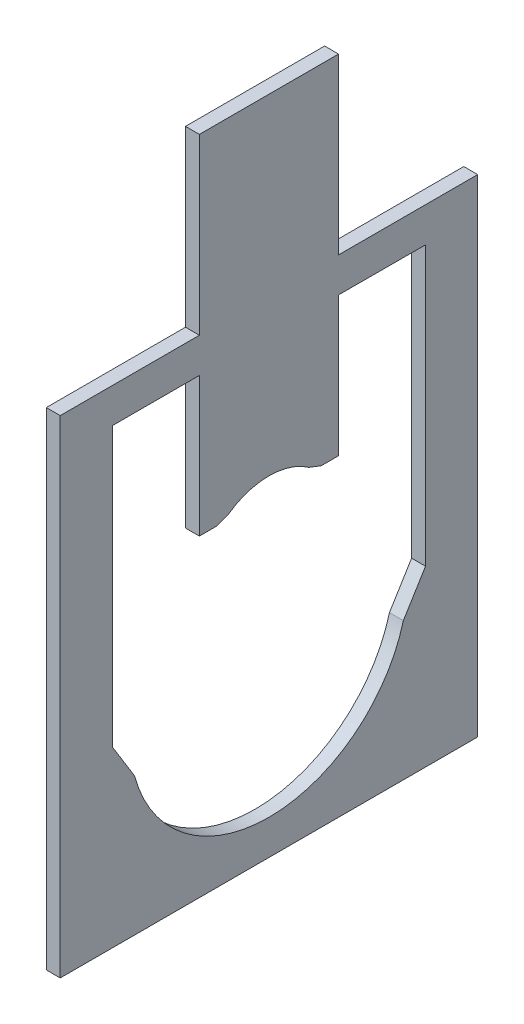
SolidWorks part; units mm, degrees
ref_plane "Front Plane" through (0, 0, 0) normal (0, 0, 1) x (1, 0, 0)
ref_plane "Top Plane" through (0, 0, 0) normal (0, 1, 0) x (1, 0, 0)
ref_plane "Right Plane" through (0, 0, 0) normal (1, 0, 0) x (0, 0, -1)
sketch "Sketch1" plane through (0, 0, 0) normal (1, 0, 0) x (0, 0, -1)
  line L0 (-29.3185, -50.1764) -> (-32.5, -45) construction
  line L5 (-29.3185, -50.1764) -> (-32.5, -45)
  line L6 (12.5, -45) -> (9.3185, -50.1764) construction
  line L7 (12.5, -45) -> (9.3185, -50.1764)
  line L16 (0, 25) -> (0, -25) construction
  line L17 (0, 25) -> (0, -25)
  line L19 (-20, 25) -> (-20, -25) construction
  line L20 (-20, 25) -> (-20, -25)
  line L21 (-34.55, -5) -> (-19.95, -5) construction
  line L22 (-32.5, -5) -> (-19.95, -5)
  line L23 (-32.5, -45) -> (-32.5, -5)
  line L24 (12.5, -45) -> (12.5, -5)
  line L25 (-4.25, -24.3185) -> (-2.5, -25) construction
  line L26 (12.5, -5) -> (0, -4.9816)
  line L27 (-20, 25) -> (0, 25)
  line L28 (0, 0) -> (20, 0)
  line L29 (20, 0) -> (20, -70)
  line L30 (20, -70) -> (-40, -70)
  line L31 (-40, -70) -> (-40, 0)
  line L32 (-40, 0) -> (-20, 0)
  line L33 (-17.5, -25) -> (-15.75, -24.3185) construction
  line L34 (-4.25, -24.3185) -> (-2.5, -25)
  line L35 (-17.5, -25) -> (-15.75, -24.3185)
  line L36 (-20, -25) -> (-17.5, -25) construction
  line L37 (-20, -25) -> (-17.5, -25)
  line L38 (-2.5, -25) -> (0, -25) construction
  line L39 (-2.5, -25) -> (0, -25)
  arc A0 (-29.3185, -50.1764) -> (9.3185, -50.1764) centre (-10, -45) ccw construction
  arc A1 (-29.3185, -50.1764) -> (9.3185, -50.1764) centre (-10, -45) ccw
  arc A2 (-4.25, -24.3185) -> (-15.75, -24.3185) centre (-10, -32.5) ccw construction
  arc A3 (-4.25, -24.3185) -> (-15.75, -24.3185) centre (-10, -32.5) ccw
  dimension "D1" = 20
  dimension "D2" = 70
extrude "Boss-Extrude1" add sketch "Sketch1" along normal blind 2
